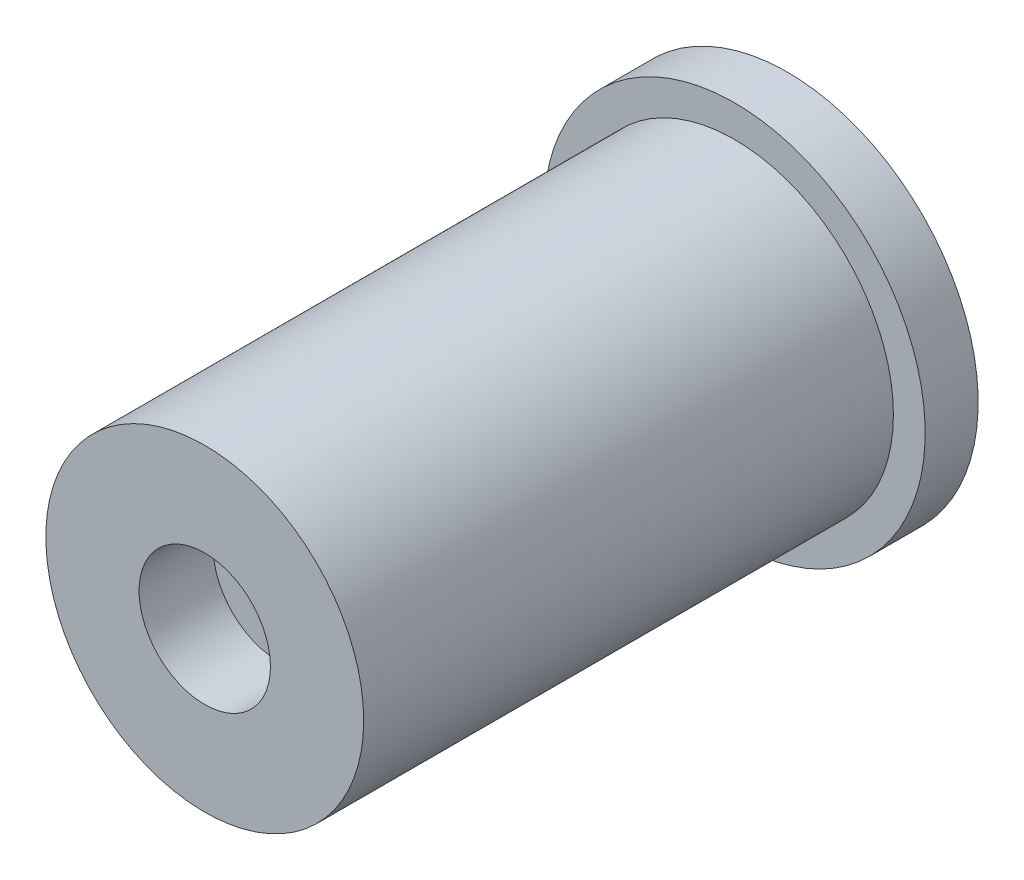
SolidWorks part; units mm, degrees
ref_plane "Alzado" through (0, 0, 0) normal (0, 0, 1) x (1, 0, 0)
ref_plane "Planta" through (0, 0, 0) normal (0, 1, 0) x (1, 0, 0)
ref_plane "Vista lateral" through (0, 0, 0) normal (1, 0, 0) x (0, 0, -1)
sketch "Croquis1" plane through (0, 0, 0) normal (0, 0, 1) x (1, 0, 0)
  circle A0 centre (0, 0) radius 7.5
  circle A1 centre (0, 0) radius 1.85
  dimension "D1" = 15
  dimension "D2" = 3.7
extrude "Saliente-Extruir1" add sketch "Croquis1" along normal blind 25
ref_plane "Plano1" through (0, 0, 12.5) normal (0, 0, 1) x (1, 0, 0)
sketch "Croquis2" plane through (0, 0, 12.5) normal (0, 0, 1) x (1, 0, 0)
  circle A0 centre (0, 0) radius 6.5
  dimension "D1" = 13
extrude "Cortar-Extruir1" cut sketch "Croquis2" against normal mid plane 15
sketch "Croquis3" plane through (0, 0, 0) normal (0, 0, -1) x (-1, 0, 0)
  circle A0 centre (0, 0) radius 9
  dimension "D1" = 18
extrude "Saliente-Extruir2" add sketch "Croquis3" along normal blind 2.5
sketch "Croquis4" plane through (0, 0, 25) normal (0, 0, 1) x (1, 0, 0)
  circle A0 centre (0, 0) radius 3.1
  dimension "D1" = 6.2
extrude "Cortar-Extruir2" cut sketch "Croquis4" against normal blind 3.5
sketch "Croquis5" plane through (0, 0, -2.5) normal (0, 0, -1) x (-1, 0, 0)
  circle A0 centre (0, 0) radius 3.075
  dimension "D1" = 6.15
extrude "Cortar-Extruir3" cut sketch "Croquis5" against normal blind 4
fillet "Redondeo1" radius 0.5 1 edges at (-3.075, 0, -2.5)
sketch "Croquis6" plane through (0, 0, -2.5) normal (0, 0, -1) x (-1, 0, 0)
  line L0 (0, 0) -> (0, 4.9613) construction
  circle A0 centre (-5.5, 0) radius 1.75
  circle A1 centre (5.5, 0) radius 1.75
  dimension "D2" = 3.5
  dimension "D1" = 5.5
extrude "Cortar-Extruir4" cut sketch "Croquis6" against normal blind 3.4
